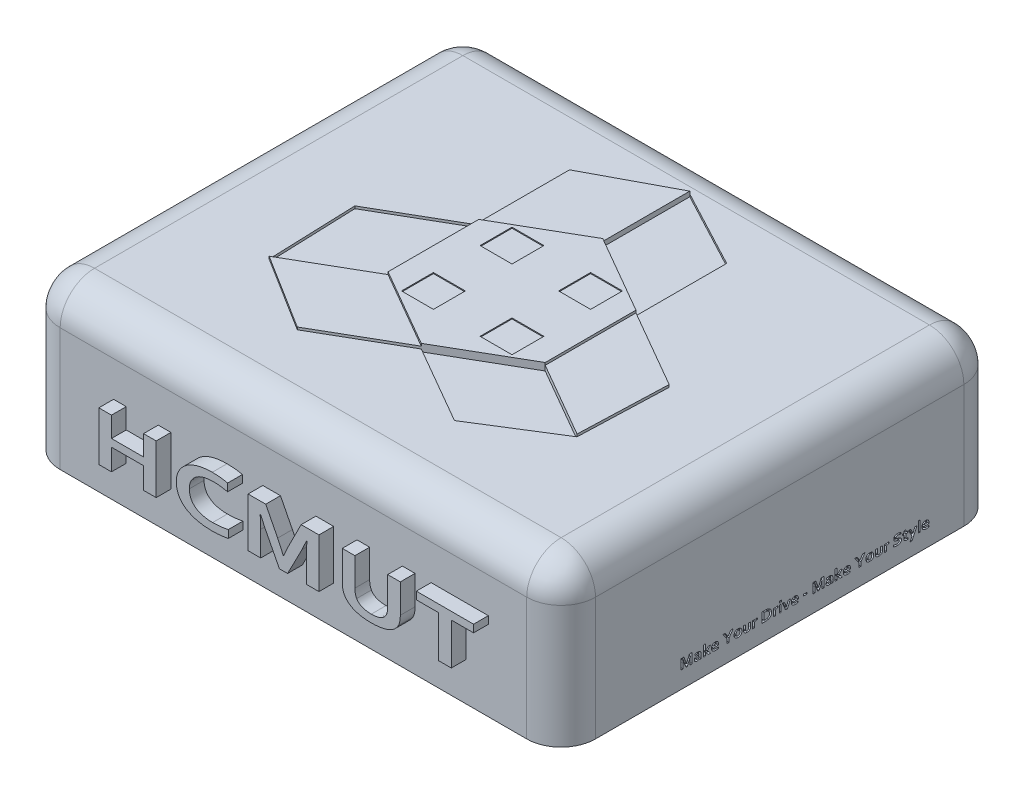
SolidWorks part; units mm, degrees
ref_plane "Front Plane" through (0, 0, 0) normal (0, 0, 1) x (1, 0, 0)
ref_plane "Top Plane" through (0, 0, 0) normal (0, 1, 0) x (1, 0, 0)
ref_plane "Right Plane" through (0, 0, 0) normal (1, 0, 0) x (0, 0, -1)
sketch "Sketch1" plane through (0, 0, 0) normal (0, 1, 0) x (1, 0, 0)
  line L1 (-52.5, 42.5) -> (52.5, 42.5)
  line L2 (-52.5, 42.5) -> (-52.5, -42.5)
  line L3 (-52.5, -42.5) -> (52.5, -42.5)
  line L4 (52.5, 42.5) -> (52.5, -42.5)
  line L5 (-52.5, 42.5) -> (52.5, -42.5) construction
  line L6 (-52.5, -42.5) -> (52.5, 42.5) construction
  point P0 (0, 0)
  dimension "D1" = 105
  dimension "D2" = 85
extrude "Boss-Extrude1" add sketch "Sketch1" along normal blind 30
fillet "Fillet1" radius 5 8 edges at (-52.5, 30, 0) (0, 30, -42.5) (52.5, 30, 0) (0, 30, 42.5) (52.5, 15, 42.5) (-52.5, 15, -42.5) (52.5, 15, -42.5) (-52.5, 15, 42.5)
shell "Shell1" thickness 2
sketch "Sketch4" plane through (0, 32, 0) normal (0, 1, 0) x (1, 0, 0)
  line L0 (0, 36.1979) -> (0, -36.1979) construction
  line L1 (-31.3483, 18.099) -> (31.3483, -18.099) construction
  line L2 (31.3483, 18.099) -> (-31.3483, -18.099) construction
  line L3 (-36.1197, -2.3785) -> (20.1197, 30.0913) construction
  line L4 (36.1197, 2.3785) -> (-20.1197, -30.0913) construction
  line L5 (-36.1197, 2.3785) -> (20.1197, -30.0913) construction
  line L6 (-20.1197, 30.0913) -> (36.1197, -2.3785) construction
  line L7 (16, 32.4698) -> (16, -32.4698) construction
  line L8 (-16, 32.4698) -> (-16, -32.4698) construction
  circle A0 centre (0, 0) radius 36.1979 construction
  dimension "D1" = 120
  dimension "D2" = 120
  dimension "D3" = 16
  dimension "D4" = 16
  dimension "D5" = 16
  dimension "D6" = 16
  dimension "D7" = 16
  dimension "D8" = 16
sketch "Sketch5" plane through (0, 32, 0) normal (0, 1, 0) x (1, 0, 0)
  line L0 (0, 18.4752) -> (-16, 9.2376)
  line L1 (0, 36.1979) -> (0, -36.1979) construction
  line L2 (-31.3483, 18.099) -> (31.3483, -18.099) construction
  line L3 (-36.1197, -2.3785) -> (20.1197, 30.0913) construction
  line L4 (-16, 9.2376) -> (-16, -9.2376)
  line L5 (31.3483, 18.099) -> (-31.3483, -18.099) construction
  line L6 (-36.1197, 2.3785) -> (20.1197, -30.0913) construction
  line L7 (-16, -9.2376) -> (0, -18.4752)
  line L8 (36.1197, 2.3785) -> (-20.1197, -30.0913) construction
  line L9 (0, -18.4752) -> (16, -9.2376)
  line L10 (16, -9.2376) -> (16, 9.2376)
  line L11 (-20.1197, 30.0913) -> (36.1197, -2.3785) construction
  line L12 (16, 9.2376) -> (0, 18.4752)
  point P8 (0, 8.0013)
extrude "Boss-Extrude3" add sketch "Sketch5" along normal blind 1
sketch "Sketch6" plane through (0, 32, 0) normal (0, 1, 0) x (1, 0, 0)
  line L0 (-16, 9.2376) -> (-16, 27.7128)
  line L1 (-20.1197, 30.0913) -> (36.1197, -2.3785) construction
  line L2 (-16, 32.4698) -> (-16, -32.4698) construction
  line L3 (-16, 27.7128) -> (0, 36.1979)
  line L4 (0, 36.1979) -> (0, 18.4752)
  line L5 (0, 18.4752) -> (-16, 9.2376)
  line L6 (16, 9.2376) -> (32, 0)
  line L7 (36.1197, 2.3785) -> (-20.1197, -30.0913) construction
  line L8 (32, 0) -> (31.3483, -18.099)
  line L9 (31.3483, -18.099) -> (16, -9.2376)
  line L10 (16, -9.2376) -> (16, 9.2376)
  line L11 (0, -18.4752) -> (-16, -27.7128)
  line L12 (-16, -27.7128) -> (-31.3483, -18.099)
  line L13 (-31.3483, -18.099) -> (-16, -9.2376)
  line L14 (-16, -9.2376) -> (0, -18.4752)
extrude "Boss-Extrude4" add sketch "Sketch6" along normal blind 0.5
sketch "Sketch7" plane through (0, 32, 0) normal (0, 1, 0) x (1, 0, 0)
  line L0 (0, 36.1979) -> (16, 27.7128)
  line L1 (-36.1197, -2.3785) -> (20.1197, 30.0913) construction
  line L2 (16, 27.7128) -> (16, 9.2376)
  line L3 (16, 9.2376) -> (0, 18.4752)
  line L4 (0, 18.4752) -> (0, 36.1979)
  line L5 (16, -9.2376) -> (31.3483, -18.099)
  line L6 (31.3483, -18.099) -> (16, -27.7128)
  line L7 (-36.1197, 2.3785) -> (20.1197, -30.0913) construction
  line L8 (16, 32.4698) -> (16, -32.4698) construction
  line L9 (16, -27.7128) -> (0, -18.4752)
  line L10 (0, -18.4752) -> (16, -9.2376)
  line L11 (-31.3483, -18.099) -> (-32, 0)
  line L12 (-32, 0) -> (-16, 9.2376)
  line L13 (-16, 9.2376) -> (-16, -9.2376)
  line L14 (-16, -9.2376) -> (-31.3483, -18.099)
  point P23 (0, 0)
  point P28 (0, 0)
  point P29 (0, 38.0313)
extrude "Cut-Extrude2" cut sketch "Sketch7" against normal blind 0.5
sketch "Sketch3" plane through (0, 32, 0) normal (0, 1, 0) x (1, 0, 0)
  line L1 (-11.25, 11.25) -> (11.25, 11.25) construction
  line L2 (-11.25, 11.25) -> (-11.25, -11.25) construction
  line L3 (-11.25, -11.25) -> (11.25, -11.25) construction
  line L4 (11.25, 11.25) -> (11.25, -11.25) construction
  line L5 (-11.25, 11.25) -> (11.25, -11.25) construction
  line L6 (-11.25, -11.25) -> (11.25, 11.25) construction
  line L7 (-11.25, 11.25) -> (-4.75, 11.25)
  line L8 (-11.25, 11.25) -> (-11.25, 4.75)
  line L9 (-11.25, 4.75) -> (-4.75, 4.75)
  line L10 (-4.75, 11.25) -> (-4.75, 4.75)
  line L11 (-11.25, 11.25) -> (-4.75, 4.75) construction
  line L12 (-11.25, 4.75) -> (-4.75, 11.25) construction
  line L13 (11.25, 11.25) -> (4.75, 11.25)
  line L14 (11.25, 11.25) -> (11.25, 4.75)
  line L15 (11.25, 4.75) -> (4.75, 4.75)
  line L16 (4.75, 11.25) -> (4.75, 4.75)
  line L17 (11.25, 11.25) -> (4.75, 4.75) construction
  line L18 (11.25, 4.75) -> (4.75, 11.25) construction
  line L19 (-11.25, -11.25) -> (-4.75, -11.25)
  line L20 (-11.25, -11.25) -> (-11.25, -4.75)
  line L21 (-11.25, -4.75) -> (-4.75, -4.75)
  line L22 (-4.75, -11.25) -> (-4.75, -4.75)
  line L23 (-11.25, -11.25) -> (-4.75, -4.75) construction
  line L24 (-11.25, -4.75) -> (-4.75, -11.25) construction
  line L25 (11.25, -11.25) -> (4.75, -11.25)
  line L26 (11.25, -11.25) -> (11.25, -4.75)
  line L27 (11.25, -4.75) -> (4.75, -4.75)
  line L28 (4.75, -11.25) -> (4.75, -4.75)
  line L29 (11.25, -11.25) -> (4.75, -4.75) construction
  line L30 (11.25, -4.75) -> (4.75, -11.25) construction
  point P4 (0, 0)
  point P10 (-8, 8)
  point P13 (8, 8)
  point P17 (-8, -8)
  point P21 (8, -8)
  point P22 (0, 0)
  dimension "D1" = 22.5
  dimension "D2" = 22.5
  dimension "D4" = 6.5
extrude "Cut-Extrude1" cut sketch "Sketch3" against normal blind 0.2 from surface at 1 starting at face at (0, 33, 0)
sketch "Sketch2" plane through (0, 0, 42.5) normal (0, 0, -1) x (-1, 0, 0)
  line L0 (38.3068, 7.829) -> (-40.9566, 7.829) construction
  text T0 "HCMUT" font "Corbel" height 10
extrude "Boss-Extrude2" add sketch "Sketch2" against normal blind 5
sketch "Sketch8" plane through (0, 0, -44.5) normal (0, 0, -1) x (-1, 0, 0)
  line L0 (19.0957, 3.472) -> (43.5717, 3.472) construction
  text T0 "AITEK" font "Corbel" height 3.5
  point P3 (19.0957, 2.5058)
extrude "Cut-Extrude3" cut sketch "Sketch8" against normal blind 1
sketch "Sketch10" plane through (54.5, 0, 0) normal (1, 0, 0) x (0, 0, -1)
  line L0 (-20.8243, 3.4246) -> (31.0573, 3.4246) construction
  text T0 "Make Your Drive - Make Your Style" font "Corbel" height 2
  point P3 (-21.1394, 5.315)
  point P4 (-20.8243, 3.4246)
extrude "Cut-Extrude4" cut sketch "Sketch10" against normal blind 0.5
